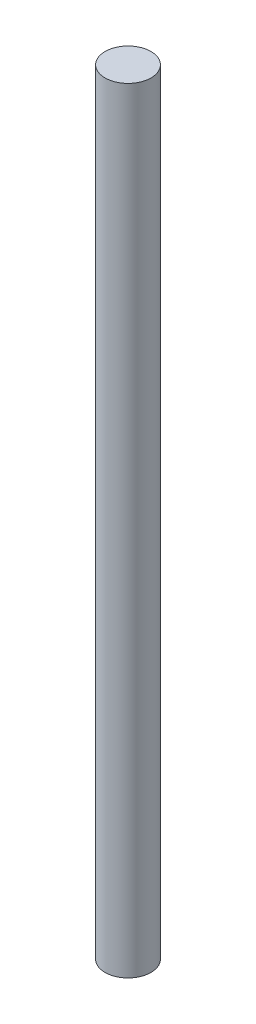
SolidWorks part; units mm, degrees
material "Plain Carbon Steel"
ref_plane "Front Plane" through (0, 0, 0) normal (0, 0, 1) x (1, 0, 0)
ref_plane "Top Plane" through (0, 0, 0) normal (0, 1, 0) x (1, 0, 0)
ref_plane "Right Plane" through (0, 0, 0) normal (1, 0, 0) x (0, 0, -1)
sketch "Sketch1" plane through (0, 0, 0) normal (0, 1, 0) x (1, 0, 0)
  circle A0 centre (0, 0) radius 3
extrude "Boss-Extrude1" add sketch "Sketch1" along normal blind 54
sketch "Sketch2" plane through (0, 54, 0) normal (0, 1, 0) x (1, 0, 0)
  circle A1 centre (0, 0) radius 3
  circle A2 centre (0, 0) radius 3
  dimension "D1" = 0
extrude "Boss-Extrude2" add sketch "Sketch2" along normal up to surface (35.2937 mm away)
sketch "Sketch3" plane through (0, 89.2937, 0) normal (0, 1, 0) x (1, 0, 0)
  circle A1 centre (0, 0) radius 3
  circle A2 centre (0, 0) radius 3
  dimension "D1" = 0
extrude "Boss-Extrude3" add sketch "Sketch3" along normal blind 6
sketch "Sketch4" plane through (0, 0, 0) normal (0, -1, 0) x (1, 0, 0)
  circle A1 centre (0, 0) radius 3
  circle A2 centre (0, 0) radius 3
  dimension "D1" = 0
extrude "Boss-Extrude4" add sketch "Sketch4" along normal blind 6
